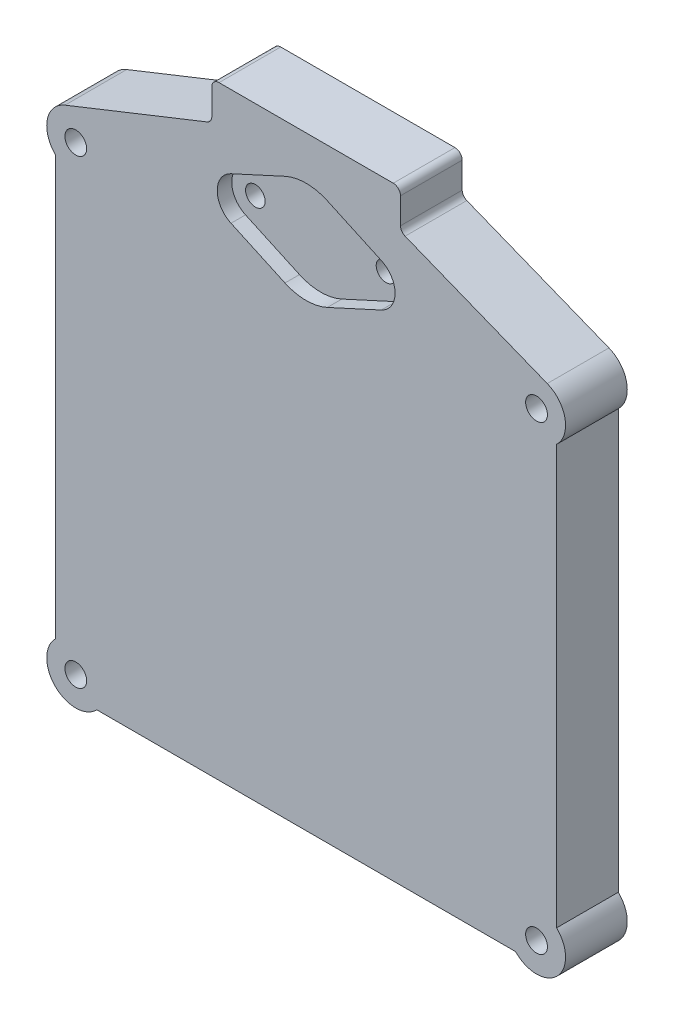
SolidWorks part; units mm, degrees
ref_plane "前视基准面" through (0, 0, 0) normal (0, 0, 1) x (1, 0, 0)
ref_plane "上视基准面" through (0, 0, 0) normal (0, 1, 0) x (1, 0, 0)
ref_plane "右视基准面" through (0, 0, 0) normal (1, 0, 0) x (0, 0, -1)
sketch "草图1" plane through (0, 0, 0) normal (0, 0, 1) x (1, 0, 0)
  line L0 (-57.6893, -69) -> (57.6893, -69)
  line L1 (69, -57.6893) -> (69, 57.6893)
  line L2 (-69, 57.6893) -> (-69, -57.6893)
  line L3 (-24, 97.5) -> (24, 97.5)
  line L4 (-27.2609, 86.4867) -> (-66.4313, 70.9086)
  line L5 (27.2609, 86.4867) -> (66.4313, 70.9086)
  line L6 (26, 88.3451) -> (26, 95.5)
  line L7 (-26, 88.3451) -> (-26, 95.5)
  arc A0 (-66.4313, 70.9086) -> (-69, 57.6893) centre (-63.4749, 63.4749) ccw
  arc A1 (69, 57.6893) -> (66.4313, 70.9086) centre (63.4749, 63.4749) ccw
  arc A2 (-69, -57.6893) -> (-57.6893, -69) centre (-63.4749, -63.4749) ccw
  arc A3 (57.6893, -69) -> (69, -57.6893) centre (63.4749, -63.4749) ccw
  arc A4 (26, 95.5) -> (24, 97.5) centre (24, 95.5) ccw
  arc A5 (-27.2609, 86.4867) -> (-26, 88.3451) centre (-28, 88.3451) ccw
  arc A6 (26, 88.3451) -> (27.2609, 86.4867) centre (28, 88.3451) ccw
  arc A7 (-24, 97.5) -> (-26, 95.5) centre (-24, 95.5) ccw
extrude "凸台-拉伸1" add sketch "草图1" along normal blind 17
sketch "草图2" plane through (0, 0, 17) normal (0, 0, 1) x (1, 0, 0)
  circle A0 centre (-63.4749, 63.4749) radius 3
  circle A1 centre (63.4749, 63.4749) radius 3
  circle A2 centre (-63.4749, -63.4749) radius 3
  circle A3 centre (63.4749, -63.4749) radius 3
extrude "切除-拉伸1" cut sketch "草图2" against normal blind 10
sketch "草图3" plane through (0, 0, 17) normal (0, 0, 1) x (1, 0, 0)
  line L0 (-20.7083, 77.4089) -> (-5.8333, 84.2268)
  line L1 (-20.7083, 65.5911) -> (-5.8333, 58.7732)
  line L2 (20.7083, 77.4089) -> (5.8333, 84.2268)
  line L3 (20.7083, 65.5911) -> (5.8333, 58.7732)
  arc A0 (-5.8333, 58.7732) -> (0, 57.5) centre (0, 71.5) ccw
  arc A1 (0, 85.5) -> (-5.8333, 84.2268) centre (0, 71.5) ccw
  arc A2 (-20.7083, 77.4089) -> (-20.7083, 65.5911) centre (-18, 71.5) ccw
  arc A3 (0, 57.5) -> (5.8333, 58.7732) centre (0, 71.5) ccw
  arc A4 (5.8333, 84.2268) -> (0, 85.5) centre (0, 71.5) ccw
  arc A5 (20.7083, 65.5911) -> (20.7083, 77.4089) centre (18, 71.5) ccw
extrude "切除-拉伸2" cut sketch "草图3" against normal blind 4
sketch "草图5" plane through (0, 0, 13) normal (0, 0, 1) x (1, 0, 0)
  circle A0 centre (-18, 71.5) radius 2.7
  circle A1 centre (18, 71.5) radius 2.7
extrude "切除-拉伸3" cut sketch "草图5" against normal blind 20
